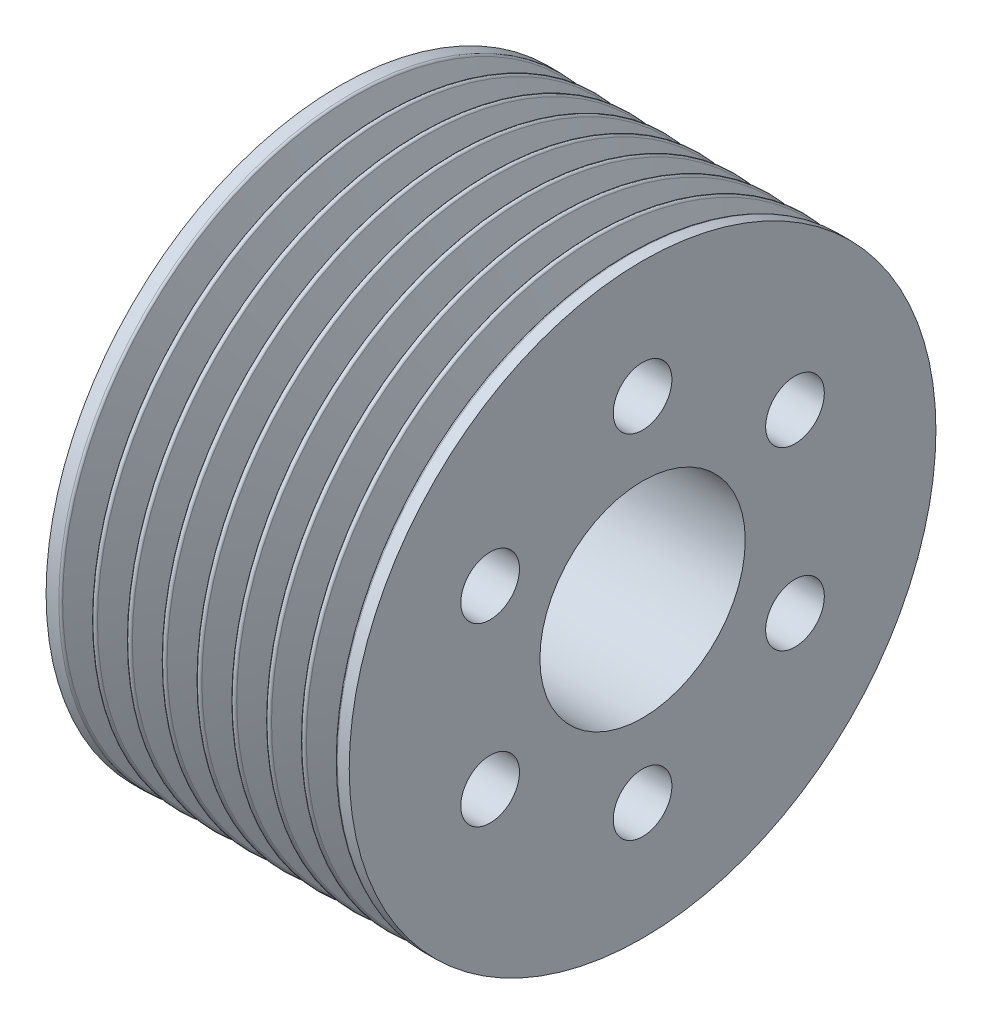
SolidWorks part; units mm, degrees
material "2018 Alloy"
ref_plane "Front Plane" through (0, 0, 0) normal (0, 0, 1) x (1, 0, 0)
ref_plane "Top Plane" through (0, 0, 0) normal (0, 1, 0) x (1, 0, 0)
ref_plane "Right Plane" through (0, 0, 0) normal (1, 0, 0) x (0, 0, -1)
sketch "Sketch1" plane through (0, 0, 0) normal (0, 0, 1) x (1, 0, 0)
  line L0 (49, 10.5) -> (49, 0) construction
  line L1 (49, 10.5) -> (49, 30)
  line L2 (49, 30) -> (18, 30)
  line L3 (18, 30) -> (18, 21.5)
  line L4 (49, 10.5) -> (31.5, 10.5)
  line L5 (0, 0) -> (49, 0) construction
  line L6 (18, 21.5) -> (31.5, 21.5)
  line L8 (0, 8.3175) -> (0, 0) construction
  line L9 (31.5, 10.5) -> (31.5, 21.5)
  dimension "D1" = 31
  dimension "D2" = 60
  dimension "D3" = 31.5
  dimension "D4" = 43
  dimension "D5" = 49
  dimension "D8" = 21
revolve "Revolve1" add sketch "Sketch1" angle 360 about L5
sketch "Sketch2" plane through (0, 0, 0) normal (0, 0, 1) x (1, 0, 0)
  line L0 (47.5458, 29.8376) -> (46.281, 26.4546)
  line L1 (45.719, 26.4546) -> (44.4542, 29.8376)
  line L2 (47.5458, 29.8376) -> (47.6066, 30) construction
  line L3 (49, 30) -> (18, 30) construction
  line L4 (44.4542, 29.8376) -> (44.3934, 30) construction
  line L5 (49, -30) -> (49, 30) construction
  line L6 (47.78, 30) -> (44.22, 30)
  line L7 (0, 0) -> (49, 0) construction
  arc A0 (47.5458, 29.8376) -> (47.78, 30) centre (47.78, 29.75) cw
  arc A1 (44.4542, 29.8376) -> (44.22, 30) centre (44.22, 29.75) ccw
  arc A2 (46.281, 26.4546) -> (45.719, 26.4546) centre (46, 26.5597) cw
  dimension "D2" = 0.25
  dimension "D3" = 0.3
  dimension "D1" = 41
  dimension "D4" = 3.56
  dimension "D5" = 3
revolve "Cut-Revolve1" cut sketch "Sketch2" angle 360 about L7
pattern_linear "LPattern1" count 8 spacing 3.56 along (-1, 0, 0) of "Cut-Revolve1"
sketch "Sketch3" plane through (49, 0, 0) normal (1, 0, 0) x (0, 0, -1)
  circle A0 centre (0, 0) radius 18 construction
  circle A1 centre (0, 18) radius 3
  circle A2 centre (15.5885, 9) radius 3
  circle A3 centre (15.5885, -9) radius 3
  circle A4 centre (0, -18) radius 3
  circle A5 centre (-15.5885, -9) radius 3
  circle A6 centre (-15.5885, 9) radius 3
  dimension "D1" = 36
  dimension "D2" = 6
  dimension "D3" = 6
extrude "Cut-Extrude1" cut sketch "Sketch3" against normal up to surface (17.5 mm away) up to face at (31.5, 0, 10.5)
